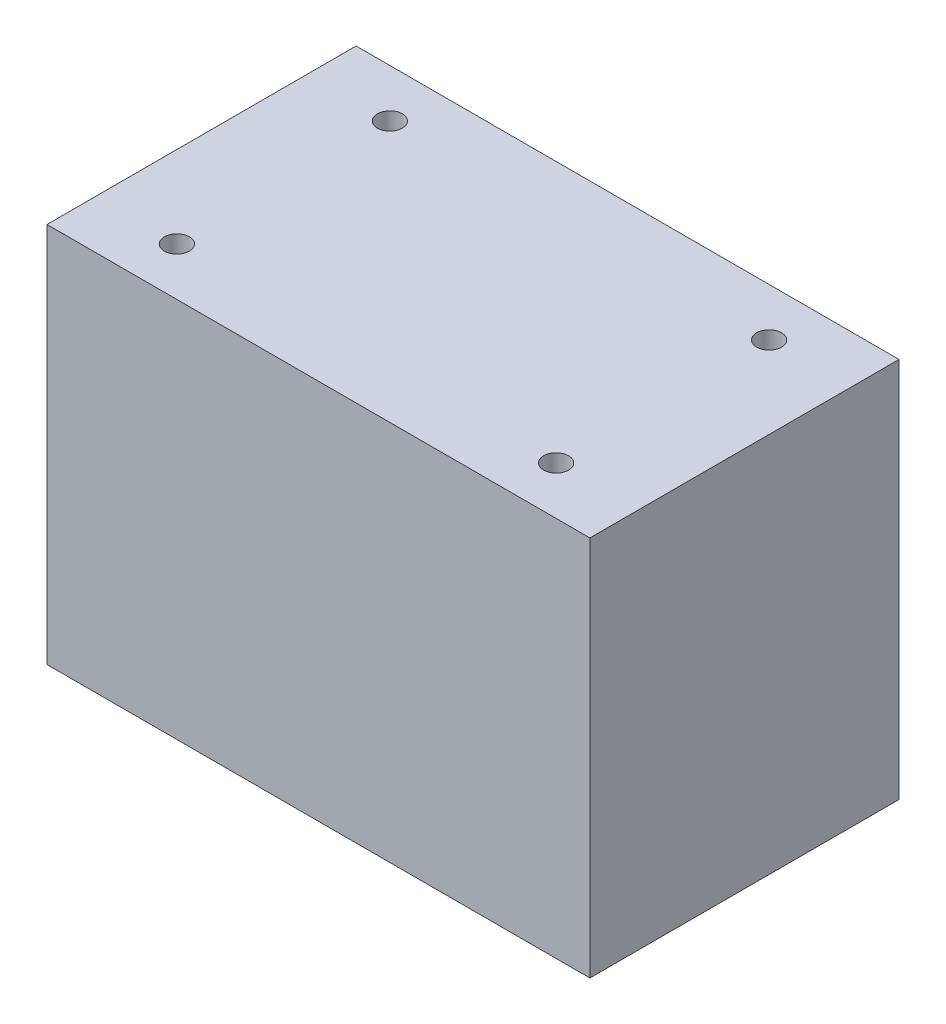
SolidWorks part; units mm, degrees
ref_plane "Front Plane" through (0, 0, 0) normal (0, 0, 1) x (1, 0, 0)
ref_plane "Top Plane" through (0, 0, 0) normal (0, 1, 0) x (1, 0, 0)
ref_plane "Right Plane" through (0, 0, 0) normal (1, 0, 0) x (0, 0, -1)
sketch "Sketch1" plane through (0, 0, 0) normal (0, 1, 0) x (1, 0, 0)
  line L1 (-52.25, -29.75) -> (52.25, -29.75)
  line L2 (-52.25, -29.75) -> (-52.25, 29.75)
  line L3 (-52.25, 29.75) -> (52.25, 29.75)
  line L4 (52.25, -29.75) -> (52.25, 29.75)
  line L5 (-52.25, -29.75) -> (52.25, 29.75) construction
  line L6 (-52.25, 29.75) -> (52.25, -29.75) construction
  point P0 (0, 0)
  dimension "D1" = 104.5
  dimension "D2" = 59.5
extrude "Boss-Extrude1" add sketch "Sketch1" along normal blind 73.36
sketch "Sketch2" plane through (0, 0, 0) normal (0, -1, 0) x (1, 0, 0)
  line L5 (-36.5, -20.5) -> (36.5, -20.5) construction
  line L7 (-36.5, -20.5) -> (-36.5, 20.5) construction
  line L8 (-36.5, 20.5) -> (36.5, 20.5) construction
  line L9 (36.5, 20.5) -> (36.5, -20.5) construction
  point P11 (-36.5, 20.5)
  point P13 (36.5, 20.5)
  point P15 (36.5, -20.5)
  point P17 (-36.5, -20.5)
  point P33 (-36.5, 0)
  point P35 (0, -20.5)
  dimension "D1" = 73
  dimension "D2" = 41
hole_wizard "CBORE for M4 SHCS2" positions "Sketch2" profile "Sketch3" counterbore size "M4" standard "ANSI Metric" end condition through all
sketch "Sketch3" plane through (-36.5, 0, 20.5) normal (1, 0, 0) x (0, 0, -1)
  line L0 (0, 0) -> (0, 73.36)
  line L1 (0, 73.36) -> (2.4, 73.36)
  line L3 (2.4, 73.36) -> (2.4, 59)
  line L4 (4, 59) -> (2.4, 59)
  line L5 (4, 59) -> (4, 0.025)
  line L6 (4, 0.025) -> (4.025, 0)
  line L7 (4.025, 0) -> (0, 0)
  line L8 (-4, 0.025) -> (-4.025, 0) construction
  line L11 (0, -6.35) -> (0, 107.95) construction
  dimension "Thru Hole Dia." = 4.8
  dimension "Thru Hole Depth" = 73.36
  dimension "C'Bore Dia." = 8
  dimension "C'Bore Depth" = 59
  dimension "Near C'Sink Dia." = 8.05
  dimension "Near C'Sink Angle" = 90
